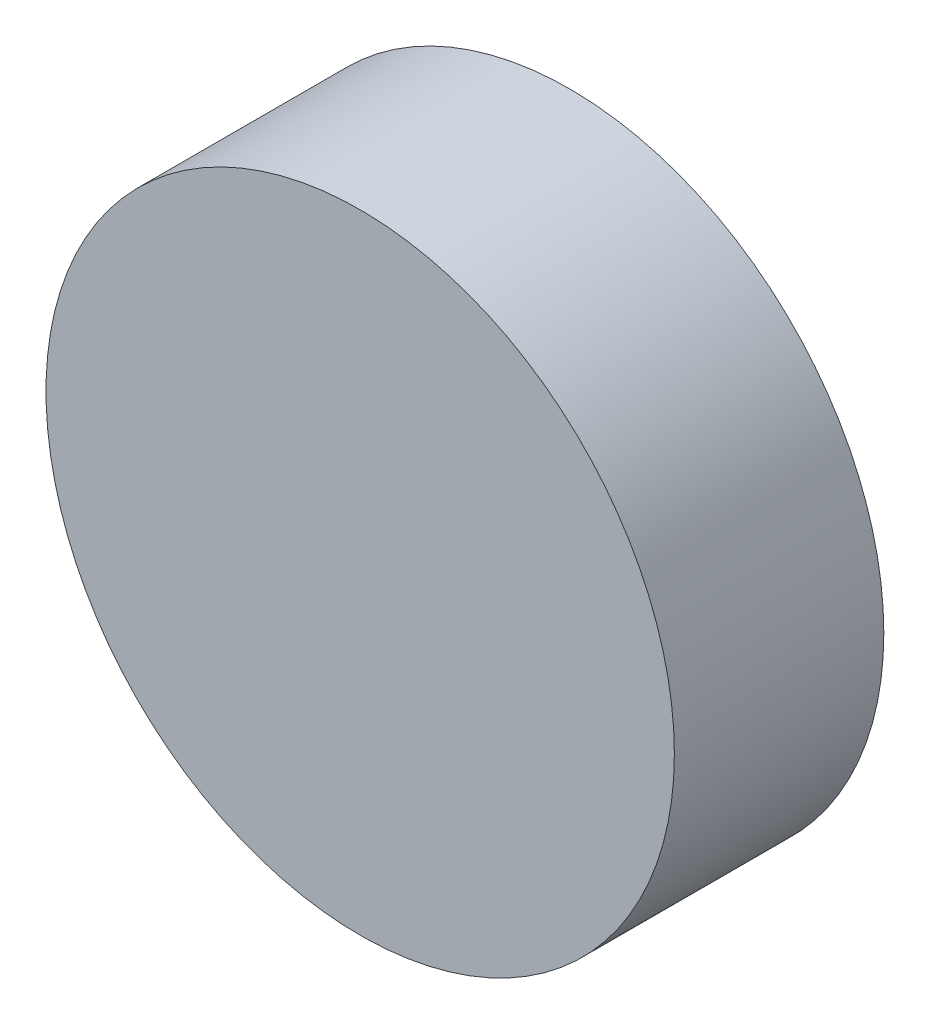
SolidWorks part; units mm, degrees
ref_plane "Front Plane" through (0, 0, 0) normal (0, 0, 1) x (1, 0, 0)
ref_plane "Top Plane" through (0, 0, 0) normal (0, 1, 0) x (1, 0, 0)
ref_plane "Right Plane" through (0, 0, 0) normal (1, 0, 0) x (0, 0, -1)
sketch "Sketch1" plane through (0, 0, 0) normal (0, 0, 1) x (1, 0, 0)
  circle A0 centre (0, 0) radius 1.5
  dimension "D1" = 3
extrude "Boss-Extrude1" add sketch "Sketch1" along normal blind 1
sketch "Sketch2" plane through (0, 0, 1) normal (0, 0, 1) x (1, 0, 0)
  point P0 (0, 0)
